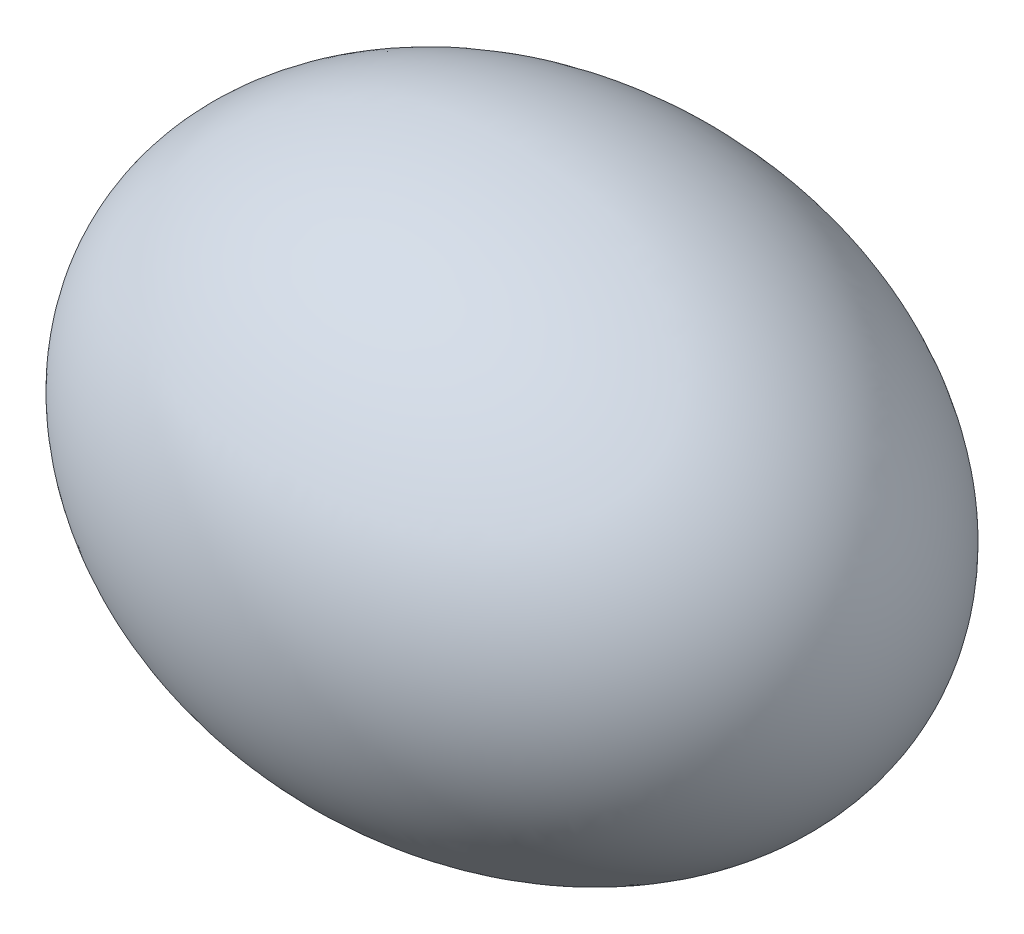
SolidWorks part; units mm, degrees
material "ABS"
ref_plane "Alzado" through (0, 0, 0) normal (0, 0, 1) x (1, 0, 0)
ref_plane "Planta" through (0, 0, 0) normal (0, 1, 0) x (1, 0, 0)
ref_plane "Vista lateral" through (0, 0, 0) normal (1, 0, 0) x (0, 0, -1)
sketch "Croquis1" plane through (0, 0, 0) normal (0, 0, 1) x (1, 0, 0)
  line L0 (-30, 0) -> (30, 0)
  ellipse E0 centre (0, 0) end of major axis (30, 0) minor radius 22.5 (-30, 0) -> (30, 0) ccw
  dimension "D1" = 45
  dimension "D2" = 60
revolve "Revolución1" add sketch "Croquis1" angle 360 about L0
ref_plane "Plano1" through (10, 0, 0) normal (1, 0, 0) x (0, 0, -1)
